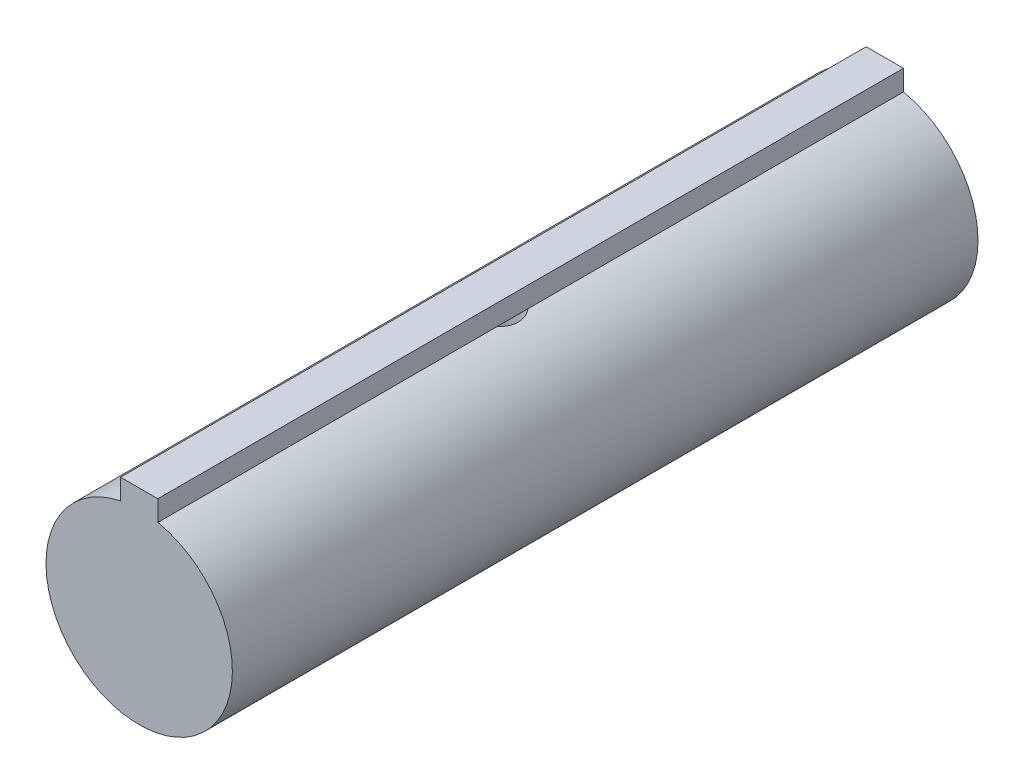
SolidWorks part; units mm, degrees
ref_plane "Front Plane" through (0, 0, 0) normal (0, 0, 1) x (1, 0, 0)
ref_plane "Top Plane" through (0, 0, 0) normal (0, 1, 0) x (1, 0, 0)
ref_plane "Right Plane" through (0, 0, 0) normal (1, 0, 0) x (0, 0, -1)
sketch "Sketch1" plane through (0, 0, 0) normal (0, 0, 1) x (1, 0, 0)
  circle A0 centre (0, 0) radius 6.35
  dimension "D1" = 12.7
extrude "Boss-Extrude1" add sketch "Sketch1" along normal blind 50.8
sketch "Sketch2" plane through (0, 0, 0) normal (0, 1, 0) x (1, 0, 0)
  circle A0 centre (0, -26.6239) radius 1.6432
extrude "Cut-Extrude1" cut sketch "Sketch2" against normal through all and the other way through all
sketch "Sketch4" plane through (0, 0, 50.8) normal (0, 0, 1) x (1, 0, 0)
  line L0 (-1.27, 6.2217) -> (-1.27, 7.62)
  line L1 (-1.27, 7.62) -> (1.27, 7.62)
  line L2 (1.27, 7.62) -> (1.27, 6.2217)
  arc A0 (1.27, 6.2217) -> (-1.27, 6.2217) centre (0, 0) ccw
  dimension "D1" = 12.7
  dimension "D2" = 7.62
  dimension "D3" = 1.27
  dimension "D4" = 2.54
extrude "Boss-Extrude2" add sketch "Sketch4" against normal blind 50.8
